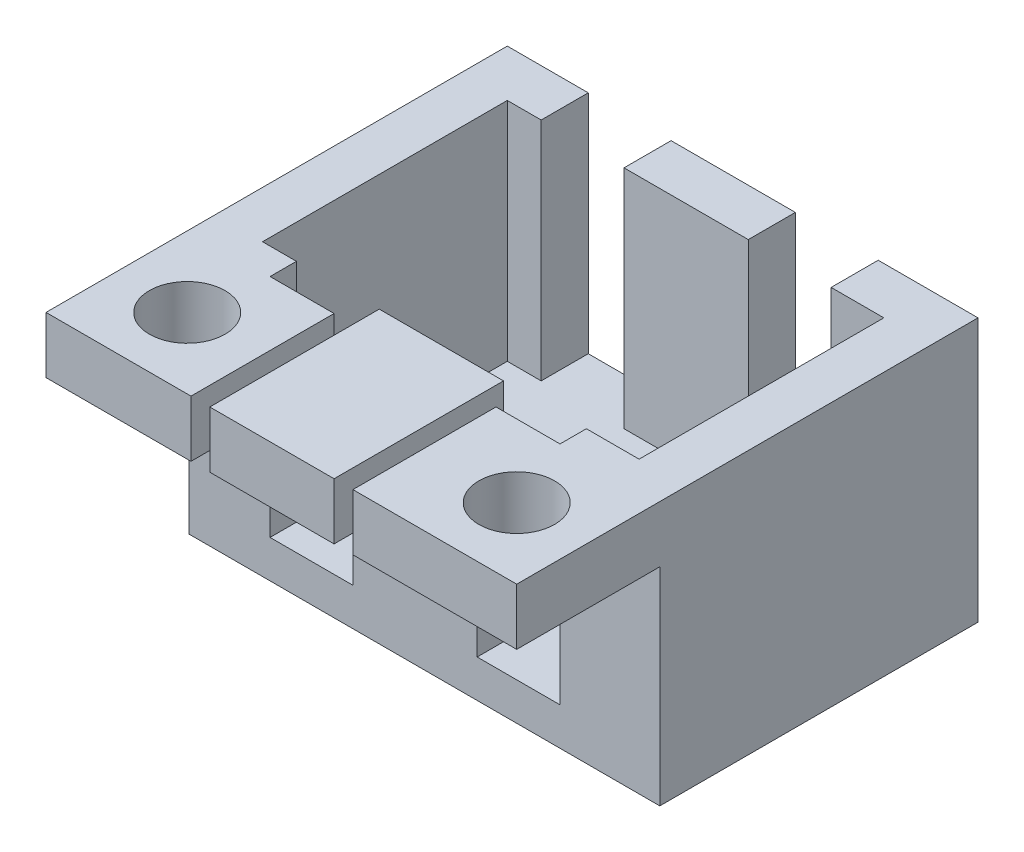
SolidWorks part; units mm, degrees
material "Delrin 2700 NC010, Low Viscosity Acetal Copolymer (SS)"
ref_plane "Front Plane" through (0, 0, 0) normal (0, 0, 1) x (1, 0, 0)
ref_plane "Top Plane" through (0, 0, 0) normal (0, 1, 0) x (1, 0, 0)
ref_plane "Right Plane" through (0, 0, 0) normal (1, 0, 0) x (0, 0, -1)
sketch "Sketch1" plane through (0, 0, 0) normal (0, 1, 0) x (1, 0, 0)
  line L0 (15.875, 10.7315) -> (-15.875, 10.7315)
  line L1 (-15.875, -10.7315) -> (15.875, -10.7315)
  line L2 (-15.875, -10.7315) -> (-15.875, 10.7315)
  line L4 (15.875, -10.7315) -> (15.875, 10.7315)
  line L5 (-15.875, -10.7315) -> (15.875, 10.7315) construction
  line L6 (-15.875, 10.7315) -> (15.875, -10.7315) construction
  point P0 (0, 0)
  dimension "D1" = 31.75
  dimension "D2" = 21.463
extrude "Plate" add sketch "Sketch1" along normal mid plane 2.54
sketch "Sketch4" plane through (0, 0, 10.7315) normal (0, 0, 1) x (1, 0, 0)
  line L1 (-15.875, 1.27) -> (15.875, 1.27)
  line L2 (-15.875, 1.27) -> (-15.875, 16.51)
  line L3 (-15.875, 16.51) -> (15.875, 16.51)
  line L4 (15.875, 1.27) -> (15.875, 16.51)
  line L5 (15.875, 1.27) -> (15.875, -1.27) construction
  dimension "D1" = 15.24
  dimension "D2" = 0
extrude "Boss-Extrude1" add sketch "Sketch4" against normal blind 1.778
sketch "Sketch5" plane through (0, 0, 8.9535) normal (0, 0, -1) x (-1, 0, 0)
  line L0 (15.875, 1.27) -> (-15.875, 1.27) construction
  line L1 (-15.875, 16.51) -> (-12.7, 16.51)
  line L2 (-15.875, 16.51) -> (-15.875, 1.27)
  line L3 (-15.875, 1.27) -> (-12.7, 1.27)
  line L4 (-12.7, 16.51) -> (-12.7, 1.27)
  line L6 (15.875, 16.51) -> (12.7, 16.51)
  line L7 (15.875, 16.51) -> (15.875, 1.27)
  line L8 (15.875, 1.27) -> (12.7, 1.27)
  line L9 (12.7, 16.51) -> (12.7, 1.27)
  dimension "D1" = 3.175
  dimension "D2" = 3.175
extrude "Boss-Extrude2" add sketch "Sketch5" along normal blind 19.685
sketch "Sketch9" plane through (12.7, 0, 0) normal (-1, 0, 0) x (0, 0, 1)
  line L0 (-10.7315, 16.51) -> (8.9535, 16.51) construction
  line L1 (-7.5565, 16.51) -> (-10.7315, 16.51)
  line L2 (-7.5565, 16.51) -> (-7.5565, 1.27)
  line L3 (-7.5565, 1.27) -> (-10.7315, 1.27)
  line L4 (-10.7315, 16.51) -> (-10.7315, 1.27)
  line L5 (-10.7315, 1.27) -> (8.9535, 1.27) construction
  line L6 (8.9535, 1.27) -> (8.9535, 16.51) construction
  dimension "D1" = 16.51
  dimension "D2" = 3.175
extrude "Boss-Extrude5" add sketch "Sketch9" along normal up to next
sketch "Sketch10" plane through (0, 0, 8.9535) normal (0, 0, -1) x (-1, 0, 0)
  line L0 (12.7, 1.27) -> (-12.7, 1.27) construction
  line L1 (-8.255, 1.27) -> (13.97, 1.27)
  line L2 (17.145, 16.51) -> (-17.145, 16.51)
  line L3 (17.145, 16.51) -> (13.97, 16.51)
  line L4 (13.97, 16.51) -> (13.97, 1.27)
  line L5 (-12.7, 16.51) -> (12.7, 16.51) construction
  line L6 (-8.255, 1.27) -> (8.255, 1.27)
  line L7 (0, 1.27) -> (0, 16.51) construction
  line L8 (-13.97, 1.27) -> (-13.97, 16.51)
  line L9 (-17.145, 16.51) -> (-13.97, 16.51)
  line L10 (-12.7, 1.27) -> (-12.7, 16.51) construction
  line L11 (8.255, 1.27) -> (-13.97, 1.27)
  dimension "D1" = 26.67
  dimension "D2" = 3.175
extrude "Boss-Extrude6" [suppressed] add sketch "Sketch10" along normal up to next
sketch "Sketch11" plane through (0, 0, -10.7315) normal (0, 0, -1) x (-1, 0, 0)
  line L0 (15.875, 16.51) -> (-15.875, 16.51) construction
  line L1 (-9.144, 16.51) -> (-3.556, 16.51)
  line L2 (-9.144, 16.51) -> (-9.144, 1.27)
  line L3 (-9.144, 1.27) -> (-3.556, 1.27)
  line L4 (-3.556, 16.51) -> (-3.556, 1.27)
  line L5 (12.7, 1.27) -> (-12.7, 1.27) construction
  line L7 (0, 1.27) -> (0, 16.51) construction
  line L12 (-15.875, 16.51) -> (-15.875, -1.27) construction
  line L13 (15.875, 16.51) -> (-15.875, 16.51) construction
  line L14 (4.826, 16.51) -> (10.414, 16.51)
  line L15 (4.826, 16.51) -> (4.826, 1.27)
  line L16 (4.826, 1.27) -> (10.414, 1.27)
  line L17 (10.414, 16.51) -> (10.414, 1.27)
  dimension "D1" = 6.731
  dimension "D2" = 5.588
  dimension "D3" = 15.24
  dimension "D4" = 20.701
  dimension "D5" = 5.588
extrude "Cut-Extrude1" cut sketch "Sketch11" against normal through all
sketch "Sketch13" plane through (0, 0, 10.7315) normal (0, 0, 1) x (1, 0, 0)
  line L0 (15.875, 16.51) -> (15.875, -1.27) construction
  line L1 (-15.875, 16.51) -> (15.875, 16.51)
  line L2 (-15.875, 16.51) -> (-15.875, 12.7)
  line L3 (-15.875, 12.7) -> (15.875, 12.7)
  line L4 (15.875, 16.51) -> (15.875, 12.7)
  dimension "D1" = 3.81
extrude "Boss-Extrude7" add sketch "Sketch13" along normal blind 9.652
hole_wizard "#10 Clearance Hole1" positions "3DSketch1" profile "Sketch14" hole size "#10" standard "ANSI Inch" end condition through all
sketch3d "3DSketch1"
  line L1 (15.875, 16.51, 20.3835) -> (-15.875, 16.51, 20.3835) construction
  line L2 (-15.875, 16.51, -10.7315) -> (-15.875, 16.51, 20.3835) construction
  point P0 (11.1125, 16.51, 15.621)
  point P4 (-11.1125, 16.51, 15.621)
  dimension "D1" = 22.225
  dimension "D2" = 4.7625
  dimension "D4" = 4.7625
sketch "Sketch14" plane through (11.1125, 16.51, 15.621) normal (1, 0, 0) x (0, 0, 1)
  line L0 (0, 0) -> (0, 17.78)
  line L1 (0, 17.78) -> (2.5527, 17.78)
  line L2 (2.5527, 17.78) -> (2.5527, 0)
  line L5 (2.5527, 0) -> (0, 0)
  line L11 (0, -6.35) -> (0, 107.95) construction
  dimension "Thru Hole Dia." = 5.1054
  dimension "Thru Hole Depth" = 17.78
sketch "Sketch16" plane through (0, 0, -10.7315) normal (0, 0, -1) x (-1, 0, 0)
  line L0 (0, 16.51) -> (0, -1.27) construction
  line L1 (-15.875, 16.51) -> (-8.89, 16.51)
  line L2 (-15.875, 16.51) -> (-15.875, 5.588)
  line L3 (-15.875, 5.588) -> (-8.89, 5.588)
  line L4 (-8.89, 16.51) -> (-8.89, 5.588)
  line L5 (4.826, 16.51) -> (-3.556, 16.51) construction
  line L6 (-15.875, -1.27) -> (15.875, -1.27) construction
  line L7 (8.89, 16.51) -> (8.89, 5.588)
  line L8 (15.875, 5.588) -> (8.89, 5.588)
  line L9 (15.875, 16.51) -> (15.875, 5.588)
  line L10 (15.875, 16.51) -> (8.89, 16.51)
  line L12 (-4.826, 16.51) -> (4.826, 16.51)
  line L13 (-4.826, 16.51) -> (-4.826, 5.588)
  line L14 (-4.826, 5.588) -> (4.826, 5.588)
  line L15 (4.826, 16.51) -> (4.826, 5.588)
  dimension "D1" = 10.922
  dimension "D2" = 6.985
  dimension "D3" = 9.652
  dimension "D4" = 10.922
  dimension "D5" = 4.826
extrude "Cut-Extrude4" [suppressed] cut sketch "Sketch16" against normal blind 9.525
sketch "Sketch18" plane through (0, 16.51, 0) normal (0, 1, 0) x (1, 0, 0)
  line L0 (15.875, -20.3835) -> (-15.875, -20.3835) construction
  line L1 (-4.826, -10.7315) -> (-6.096, -10.7315)
  line L2 (-4.826, -10.7315) -> (-4.826, -20.3835)
  line L3 (-4.826, -20.3835) -> (-6.096, -20.3835)
  line L4 (-6.096, -10.7315) -> (-6.096, -20.3835)
  line L6 (3.556, -10.7315) -> (4.826, -10.7315)
  line L7 (3.556, -10.7315) -> (3.556, -20.3835)
  line L8 (3.556, -20.3835) -> (4.826, -20.3835)
  line L9 (4.826, -10.7315) -> (4.826, -20.3835)
  dimension "D1" = 1.27
  dimension "D2" = 1.27
extrude "Cut-Extrude6" cut sketch "Sketch18" against normal through all
sketch "Sketch19" [suppressed] plane through (0, 5.588, 0) normal (0, 1, 0) x (1, 0, 0)
  line L1 (-4.826, 10.7315) -> (3.556, 10.7315)
  line L2 (-4.826, 10.7315) -> (-4.826, 7.5565)
  line L3 (-4.826, 7.5565) -> (3.556, 7.5565)
  line L4 (3.556, 10.7315) -> (3.556, 7.5565)
  line L5 (-4.826, 10.7315) -> (3.556, 7.5565) construction
  line L6 (-4.826, 7.5565) -> (3.556, 10.7315) construction
  point P4 (-0.635, 9.144)
extrude "Boss-Extrude8" [suppressed] add sketch "Sketch19" along normal up to surface (10.922 mm away)
